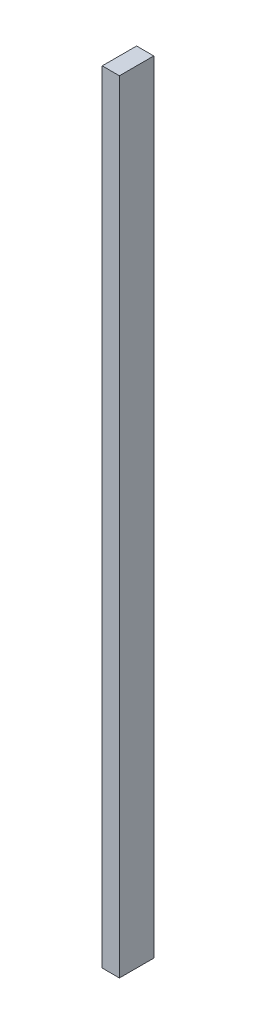
SolidWorks part; units mm, degrees
ref_plane "Front Plane" through (0, 0, 0) normal (0, 0, 1) x (1, 0, 0)
ref_plane "Top Plane" through (0, 0, 0) normal (0, 1, 0) x (1, 0, 0)
ref_plane "Right Plane" through (0, 0, 0) normal (1, 0, 0) x (0, 0, -1)
sketch "Sketch1" plane through (0, 0, 0) normal (0, 1, 0) x (1, 0, 0)
  line L1 (-12.7, -25.4) -> (12.7, -25.4)
  line L2 (-12.7, -25.4) -> (-12.7, 25.4)
  line L3 (-12.7, 25.4) -> (12.7, 25.4)
  line L4 (12.7, -25.4) -> (12.7, 25.4)
  line L5 (-12.7, -25.4) -> (12.7, 25.4) construction
  line L6 (-12.7, 25.4) -> (12.7, -25.4) construction
  point P0 (0, 0)
  dimension "D1" = 25.4
  dimension "D2" = 50.8
extrude "Boss-Extrude1" add sketch "Sketch1" along normal blind 1155.192
